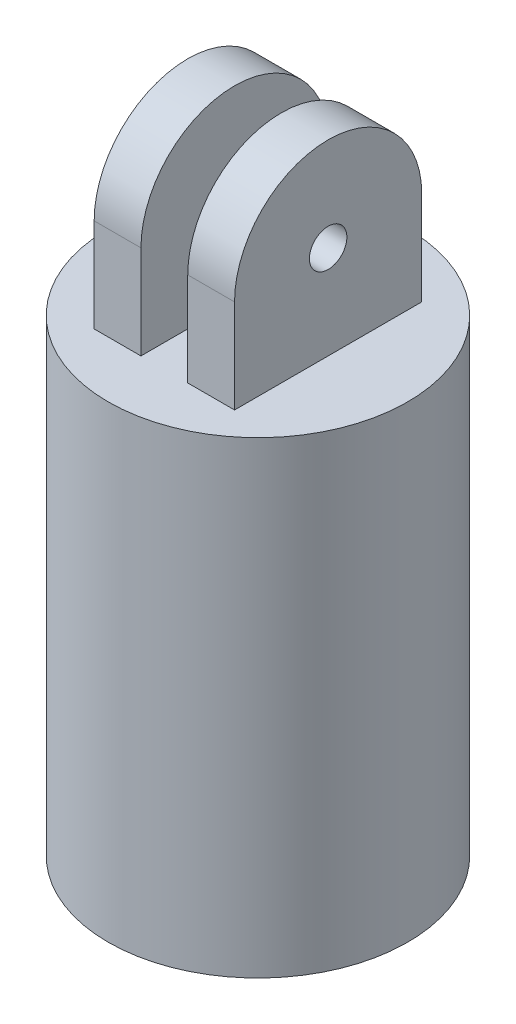
SolidWorks part; units mm, degrees
ref_plane "Front Plane" through (0, 0, 0) normal (0, 0, 1) x (1, 0, 0)
ref_plane "Top Plane" through (0, 0, 0) normal (0, 1, 0) x (1, 0, 0)
ref_plane "Right Plane" through (0, 0, 0) normal (1, 0, 0) x (0, 0, -1)
sketch "Sketch1" plane through (0, 0, 0) normal (0, 1, 0) x (1, 0, 0)
  circle A0 centre (0, 0) radius 12.7
  circle A1 centre (0, 0) radius 16
extrude "Boss-Extrude1" add sketch "Sketch1" along normal blind 40
sketch "Sketch2" plane through (0, 40, 0) normal (0, 1, 0) x (1, 0, 0)
  circle A0 centre (0, 0) radius 16
extrude "Boss-Extrude2" add sketch "Sketch2" along normal blind 10
sketch "Sketch3" plane through (0, 50, 0) normal (0, 1, 0) x (1, 0, 0)
  line L0 (0, 0) -> (0, 16)
  line L1 (0, 16) -> (0, -16)
  line L2 (0, -16) -> (0, 0)
  line L3 (-2.5, 10) -> (2.5, 10)
  line L4 (-2.5, 10) -> (2.5, 10)
  line L5 (-2.5, 10) -> (-2.5, -10)
  line L6 (-2.5, -10) -> (2.5, -10)
  line L7 (2.5, 10) -> (2.5, -10)
  line L8 (-2.5, 10) -> (2.5, -10) construction
  line L9 (-2.5, -10) -> (2.5, 10) construction
  line L10 (2.5, 10) -> (7.5, 10)
  line L11 (7.5, 10) -> (7.5, -10)
  line L12 (7.5, -10) -> (2.5, -10)
  line L13 (-2.5, 10) -> (-7.5, 10)
  line L14 (-7.5, 10) -> (-7.5, -10)
  line L15 (-7.5, -10) -> (-2.5, -10)
  circle A0 centre (0, 0) radius 16 construction
extrude "Boss-Extrude3" add sketch "Sketch3" along normal blind 20 contours L14 L15 L5 L13 | L12 L11 L10 L7
sketch "Sketch4" plane through (2.5, 0, 0) normal (-1, 0, 0) x (0, 0, 1)
  line L0 (-10, 70) -> (10, 70)
  line L1 (10, 70) -> (0, 70)
  line L2 (0, 70) -> (0, 50)
  line L3 (16, 50) -> (-16, 50) construction
  line L4 (10, 70) -> (10, 50) construction
  line L5 (-10, 70) -> (-10, 50) construction
  line L6 (-10, 60) -> (-10, 70)
  line L7 (10, 70) -> (10, 60)
  arc A0 (0, 70) -> (10, 60) centre (0, 60) cw
  arc A1 (0, 70) -> (-10, 60) centre (0, 60) ccw
  circle A2 centre (0, 60) radius 2
extrude "Cut-Extrude1" cut sketch "Sketch4" against normal blind 5 and the other way blind 15
